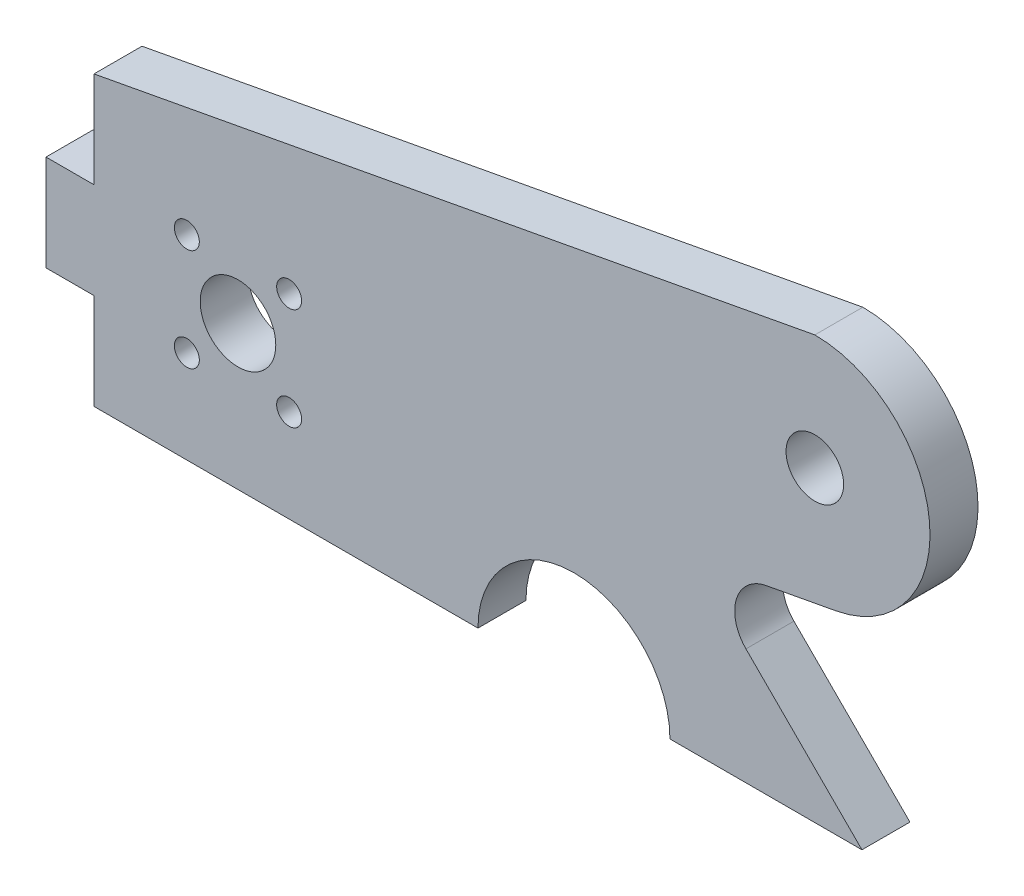
SolidWorks part; units mm, degrees
ref_plane "Front Plane" through (0, 0, 0) normal (0, 0, 1) x (1, 0, 0)
ref_plane "Top Plane" through (0, 0, 0) normal (0, 1, 0) x (1, 0, 0)
ref_plane "Right Plane" through (0, 0, 0) normal (1, 0, 0) x (0, 0, -1)
sketch "Sketch1" plane through (0, 0, 0) normal (0, 0, 1) x (1, 0, 0)
  line L0 (0, 0) -> (101.6, 0)
  line L3 (0, 38.1) -> (0, 25.4)
  line L4 (95.3675, 55.88) -> (0, 38.1)
  line L5 (0, 19.05) -> (100.2273, 19.05) construction
  line L6 (19.05, 19.05) -> (19.05, 28.62) construction
  line L7 (19.05, 19.05) -> (25.817, 25.817) construction
  line L8 (101.6, 0) -> (79.4333, 22.1667)
  line L9 (79.4333, 22.1667) -> (98.1606, 25.6582)
  line L10 (0, 12.7) -> (0, 0)
  line L11 (0, 25.4) -> (-6.35, 25.4)
  line L13 (0, 12.7) -> (-6.35, 12.7)
  line L14 (-6.35, 25.4) -> (-6.35, 12.7)
  arc A0 (98.1606, 25.6582) -> (95.3675, 55.88) centre (95.3675, 40.64) ccw
  circle A1 centre (95.3675, 40.64) radius 3.81
  circle A2 centre (19.05, 19.05) radius 9.57 construction
  circle A3 centre (25.817, 25.817) radius 1.651
  circle A4 centre (25.817, 12.283) radius 1.651
  circle A5 centre (12.283, 12.283) radius 1.651
  circle A6 centre (12.283, 25.817) radius 1.651
  point P26 (19.05, 19.05)
  dimension "D1" = 7.62
  dimension "D5" = 15.24
  dimension "D4" = 19.14
  dimension "D7" = 3.302
  dimension "D11" = 19.05
  dimension "D2" = 38.1
  dimension "D3" = 40.64
  dimension "D6" = 101.6
  dimension "D8" = 45
  dimension "D9" = 4
  dimension "D10" = 19.05
  dimension "D12" = 45
  dimension "D13" = 0
  dimension "D14" = 12.7
  dimension "D15" = 12.7
  dimension "D16" = 6.35
extrude "Boss-Extrude1" add sketch "Sketch1" along normal blind 6.35
sketch "Sketch2" plane through (0, 0, 6.35) normal (0, 0, 1) x (1, 0, 0)
  circle A0 centre (95.3675, 40.64) radius 38.1 construction
fillet "Fillet2" radius 5.08 1 edges at (79.4333, 22.1667, 3.175)
sketch "Sketch3" plane through (0, 0, 0) normal (-1, 0, 0) x (0, 0, 1)
  line L0 (0, 38.1) -> (6.35, 25.4) construction
  line L1 (6.35, 12.7) -> (0, 0) construction
  circle A0 centre (3.175, 31.75) radius 1.5875
  circle A1 centre (3.175, 6.35) radius 1.5875
  dimension "D1" = 3.175
  dimension "D2" = 3.175
extrude "Cut-Extrude1" cut sketch "Sketch3" against normal blind 6.35
sketch "Sketch6" plane through (0, 0, 6.35) normal (0, 0, 1) x (1, 0, 0)
  line L0 (0, 0) -> (101.6, 0) construction
  line L1 (50.8, 0) -> (76.2, 0)
  arc A0 (76.2, 0) -> (50.8, 0) centre (63.5, 0) ccw
  dimension "D1" = 25.4
  dimension "D2" = 25.4
extrude "Cut-Extrude2" cut sketch "Sketch6" against normal blind 6.35
sketch "Sketch7" plane through (0, 0, 6.35) normal (0, 0, 1) x (1, 0, 0)
  line L0 (12.283, 25.817) -> (25.817, 12.283) construction
  line L1 (12.283, 12.283) -> (25.817, 25.817) construction
  circle A0 centre (19.05, 19.05) radius 5
  dimension "D1" = 10
extrude "Cut-Extrude3" cut sketch "Sketch7" against normal through all
